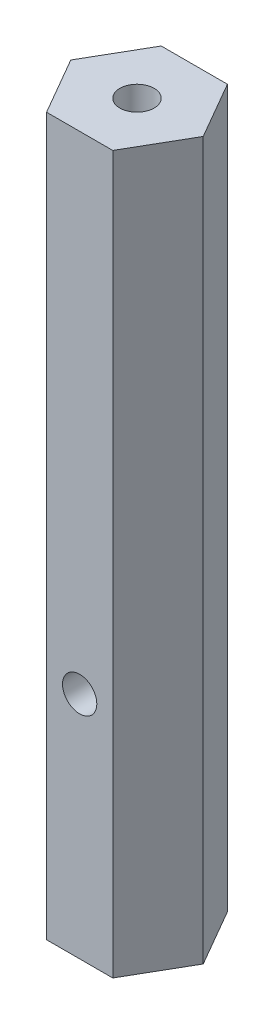
SolidWorks part; units mm, degrees
material "AISI 304"
ref_plane "Front Plane" through (0, 0, 0) normal (0, 0, 1) x (1, 0, 0)
ref_plane "Top Plane" through (0, 0, 0) normal (0, 1, 0) x (1, 0, 0)
ref_plane "Right Plane" through (0, 0, 0) normal (1, 0, 0) x (0, 0, -1)
sketch "Sketch1" plane through (0, 0, 0) normal (0, 1, 0) x (1, 0, 0)
  line L1 (7.3323, 0) -> (3.6662, 6.35)
  line L2 (3.6662, 6.35) -> (-3.6662, 6.35)
  line L3 (-3.6662, 6.35) -> (-7.3323, 0)
  line L4 (-7.3323, 0) -> (-3.6662, -6.35)
  line L5 (-3.6662, -6.35) -> (3.6662, -6.35)
  line L6 (3.6662, -6.35) -> (7.3323, 0)
  circle A0 centre (0, 0) radius 6.35 construction
  dimension "D1" = 12.7
extrude "Boss-Extrude1" add sketch "Sketch1" along normal blind 79.375 contours L1 L2 L3 L4 L5 L6
hole_wizard "Tap Drill for #10-24 Tap1" positions "Sketch2" profile "Sketch3" hole size "#10-24" standard "ANSI Inch"
sketch "Sketch2" plane through (0, 79.375, 0) normal (0, 1, 0) x (1, 0, 0)
  point P0 (0, 0)
sketch "Sketch3" plane through (0, 79.375, 0) normal (1, 0, 0) x (0, 0, 1)
  line L0 (0, 0) -> (0, 26.5408)
  line L1 (0, 26.5408) -> (1.8986, 25.4)
  line L2 (1.8986, 25.4) -> (1.8986, 0)
  line L5 (1.8986, 0) -> (0, 0)
  line L10 (0, 26.5408) -> (-1.8986, 25.4) construction
  line L11 (0, -6.35) -> (0, 107.95) construction
  dimension "Hole Dia." = 3.7973
  dimension "Hole Depth" = 25.4
  dimension "Drill Angle" = 118
hole_wizard "Tap Drill for #10-24 Tap2" positions "Sketch5" profile "Sketch6" hole size "#10-24" standard "ANSI Inch"
sketch "Sketch5" plane through (0, 0, 6.35) normal (0, 0, 1) x (1, 0, 0)
  line L0 (-3.6662, 0) -> (3.6662, 0) construction
  line L1 (-3.6662, 0) -> (3.6662, 0) construction
  point P0 (0, 25.4)
  point P7 (0, 0)
  dimension "D1" = 25.4
sketch "Sketch6" plane through (0, 25.4, 6.35) normal (1, 0, 0) x (0, -1, 0)
  line L0 (0, 0) -> (0, 26.5408)
  line L1 (0, 26.5408) -> (1.8986, 25.4)
  line L2 (1.8986, 25.4) -> (1.8986, 0)
  line L5 (1.8986, 0) -> (0, 0)
  line L10 (0, 26.5408) -> (-1.8986, 25.4) construction
  line L11 (0, -6.35) -> (0, 107.95) construction
  dimension "Hole Dia." = 3.7973
  dimension "Hole Depth" = 25.4
  dimension "Drill Angle" = 118
